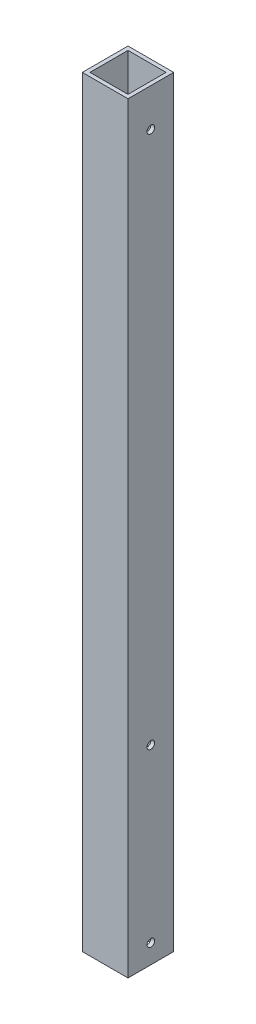
SolidWorks part; units mm, degrees
ref_plane "前视基准面" through (0, 0, 0) normal (0, 0, 1) x (1, 0, 0)
ref_plane "上视基准面" through (0, 0, 0) normal (0, 1, 0) x (1, 0, 0)
ref_plane "右视基准面" through (0, 0, 0) normal (1, 0, 0) x (0, 0, -1)
sketch "草图1" plane through (0, 0, 0) normal (0, 1, 0) x (1, 0, 0)
  line L1 (0, 0) -> (12, 0)
  line L2 (0, 0) -> (0, 12)
  line L3 (0, 12) -> (12, 12)
  line L4 (12, 0) -> (12, 12)
  line L5 (2, 2) -> (10, 2)
  line L6 (2, 2) -> (2, 10)
  line L7 (2, 10) -> (10, 10)
  line L8 (10, 2) -> (10, 10)
  point P5 (2, 2)
extrude "凸台-拉伸1" add sketch "草图1" along normal blind 200
sketch "草图2" plane through (0, 0, 0) normal (-1, 0, 0) x (0, 0, 1)
  line L0 (0, 200) -> (0, 190)
  line L1 (0, 200) -> (0, 0) construction
  line L2 (0, 190) -> (-12, 190)
  line L3 (-12, 200) -> (-12, 0) construction
  circle A0 centre (-6, 190) radius 1
  point P5 (-6, 190)
extrude "切除-拉伸1" cut sketch "草图2" against normal blind 12 contours L2 A0 | L2 A0
sketch "草图3" plane through (0, 0, -12) normal (0, 0, -1) x (-1, 0, 0)
  circle A0 centre (-6, 5) radius 1
  point P0 (-6, 5)
sketch "草图4" plane through (0, 0, 0) normal (0, -1, 0) x (-1, 0, 0)
  line L3 (-11, 6) -> (-11, 1)
  line L4 (-11, 1) -> (-1, 1)
  line L5 (-1, 1) -> (-1, 11)
  line L6 (-1, 11) -> (-11, 11)
  line L7 (-11, 11) -> (-11, 6)
extrude "切除-拉伸3" cut sketch "草图4" against normal blind 200
sketch "草图5" plane through (0, 0, 0) normal (0, 0, 1) x (1, 0, 0)
  circle A0 centre (6, 5) radius 1
sketch "草图6" plane through (12, 0, 0) normal (1, 0, 0) x (0, 0, -1)
  circle A0 centre (6, 5) radius 1
extrude "切除-拉伸4" cut sketch "草图6" against normal blind 12
sketch "草图7" plane through (0, 0, 0) normal (-1, 0, 0) x (0, 0, 1)
  circle A0 centre (-6, 50) radius 1
  point P0 (-6, 50)
extrude "切除-拉伸5" cut sketch "草图7" against normal blind 12
